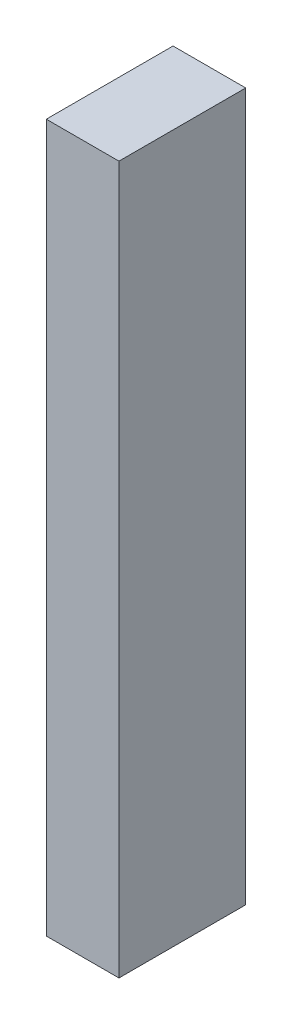
SolidWorks part; units mm, degrees
ref_plane "Přední rovina" through (0, 0, 0) normal (0, 0, 1) x (1, 0, 0)
ref_plane "Horní rovina" through (0, 0, 0) normal (0, 1, 0) x (1, 0, 0)
ref_plane "Pravá rovina" through (0, 0, 0) normal (1, 0, 0) x (0, 0, -1)
sketch "Skica1" plane through (0, 0, 0) normal (0, 0, 1) x (1, 0, 0)
  line L1 (2.465, 24) -> (-2.465, 24)
  line L2 (2.465, 24) -> (2.465, -24)
  line L3 (2.465, -24) -> (-2.465, -24)
  line L4 (-2.465, 24) -> (-2.465, -24)
  line L5 (2.465, 24) -> (-2.465, -24) construction
  line L6 (2.465, -24) -> (-2.465, 24) construction
  point P0 (0, 0)
  dimension "D1" = 48
  dimension "D2" = 4.93
extrude "Přidat vysunutím1" add sketch "Skica1" along normal blind 8.6
